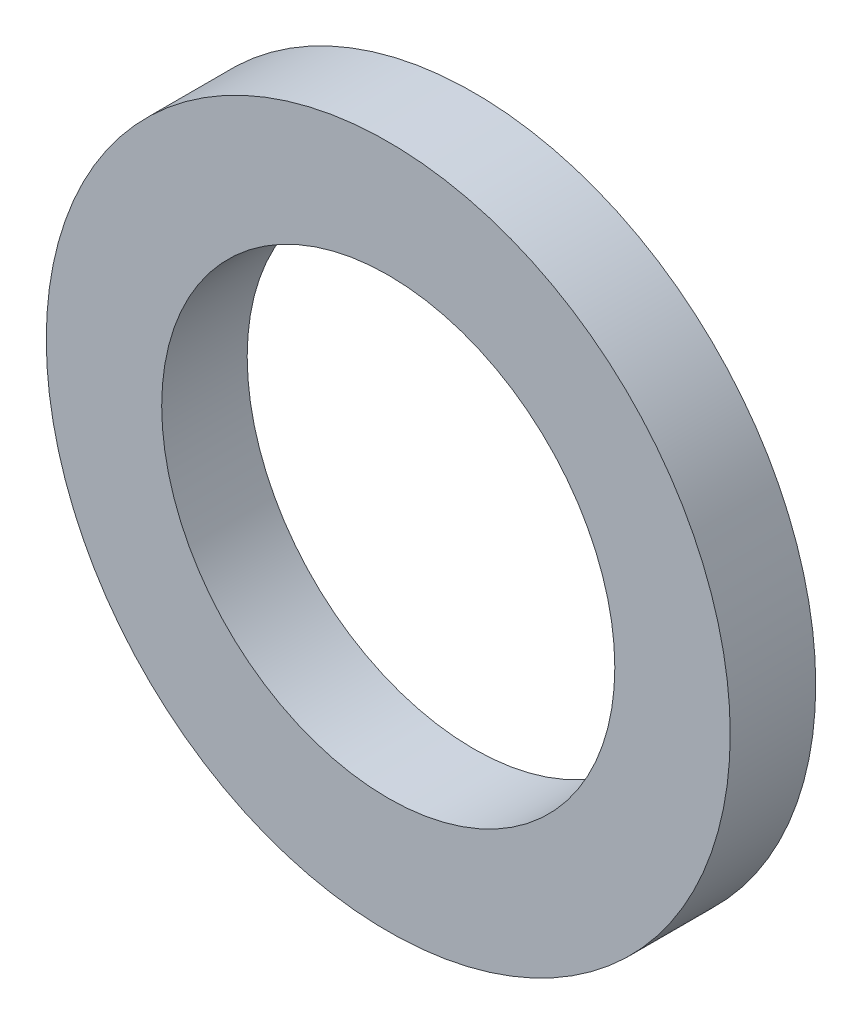
SolidWorks part; units mm, degrees
ref_plane "Front Plane" through (0, 0, 0) normal (0, 0, 1) x (1, 0, 0)
ref_plane "Top Plane" through (0, 0, 0) normal (0, 1, 0) x (1, 0, 0)
ref_plane "Right Plane" through (0, 0, 0) normal (1, 0, 0) x (0, 0, -1)
sketch "Sketch1" plane through (0, 0, 0) normal (0, 0, 1) x (1, 0, 0)
  circle A0 centre (0, 0) radius 4
extrude "Boss-Extrude1" add sketch "Sketch1" along normal blind 1
sketch "Sketch2" plane through (0, 0, 1) normal (0, 0, 1) x (1, 0, 0)
  circle A0 centre (0, 0) radius 2.65
extrude "Cut-Extrude1" cut sketch "Sketch2" against normal up to next
